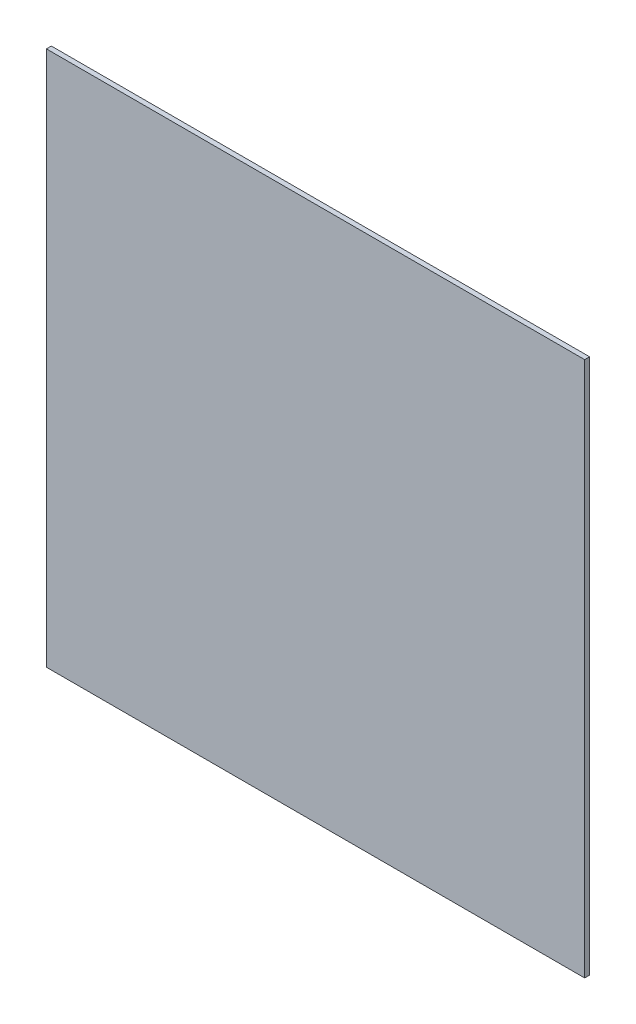
SolidWorks part; units mm, degrees
ref_plane "Front Plane" through (0, 0, 0) normal (0, 0, 1) x (1, 0, 0)
ref_plane "Top Plane" through (0, 0, 0) normal (0, 1, 0) x (1, 0, 0)
ref_plane "Right Plane" through (0, 0, 0) normal (1, 0, 0) x (0, 0, -1)
sketch "Sketch1" plane through (0, 0, 0) normal (0, 0, 1) x (1, 0, 0)
  line L1 (-304.8, -303.2125) -> (304.8, -303.2125)
  line L2 (-304.8, -303.2125) -> (-304.8, 303.2125)
  line L3 (-304.8, 303.2125) -> (304.8, 303.2125)
  line L4 (304.8, -303.2125) -> (304.8, 303.2125)
  line L5 (-304.8, -303.2125) -> (304.8, 303.2125) construction
  line L6 (-304.8, 303.2125) -> (304.8, -303.2125) construction
  point P0 (0, 0)
  dimension "D1" = 609.6
  dimension "D2" = 606.425
extrude "Boss-Extrude1" add sketch "Sketch1" along normal blind 5.588
